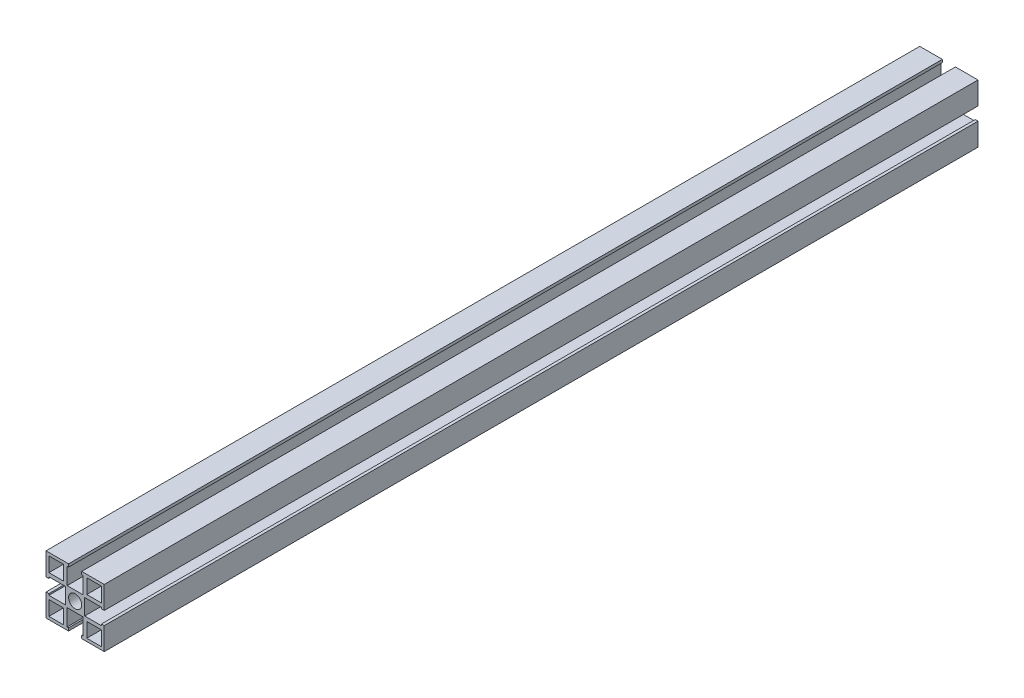
SolidWorks part; units mm, degrees
ref_plane "前视基准面" through (0, 0, 0) normal (0, 0, 1) x (1, 0, 0)
ref_plane "上视基准面" through (0, 0, 0) normal (0, 1, 0) x (1, 0, 0)
ref_plane "右视基准面" through (0, 0, 0) normal (1, 0, 0) x (0, 0, -1)
sketch "草图1" plane through (0, 0, 0) normal (0, 0, 1) x (1, 0, 0)
  line L0 (-2.3693, 20) -> (20, 20) construction
  line L1 (0, 0) -> (15.5, 0)
  line L2 (0, 0) -> (0, 15.5)
  line L3 (0, 40) -> (15.5, 40)
  line L4 (40, 0) -> (40, 15.5)
  line L5 (20, -2.0156) -> (20, 42.823) construction
  line L6 (24.5, 40) -> (40, 40)
  line L7 (14.5, 26.5504) -> (25.5, 26.5504)
  line L8 (14.5, 26.5504) -> (14.5, 38.0504)
  line L9 (2, 38) -> (12, 38)
  line L10 (2, 38) -> (2, 28)
  line L11 (2, 28) -> (12, 28)
  line L12 (12, 38) -> (12, 28)
  line L13 (2, 2) -> (12, 2)
  line L14 (2, 2) -> (2, 12)
  line L15 (2, 12) -> (12, 12)
  line L16 (12, 2) -> (12, 12)
  line L17 (38, 38) -> (28, 38)
  line L18 (38, 38) -> (38, 28)
  line L19 (38, 28) -> (28, 28)
  line L20 (28, 38) -> (28, 28)
  line L21 (38, 2) -> (28, 2)
  line L22 (38, 2) -> (38, 12)
  line L23 (38, 12) -> (28, 12)
  line L24 (28, 2) -> (28, 12)
  line L25 (14.5, 38.0504) -> (15.5, 38.0504)
  line L26 (25.5, 26.5504) -> (25.5, 38.0504)
  line L27 (24.5, 38.0504) -> (25.5, 38.0504)
  line L28 (15.5, 38.0504) -> (15.5, 40)
  line L29 (24.5, 1.9496) -> (24.5, 0)
  line L30 (24.5, 38.0504) -> (24.5, 40)
  line L31 (15.5, 1.9496) -> (15.5, 0)
  line L32 (24.5, 1.9496) -> (25.5, 1.9496)
  line L33 (25.5, 13.4496) -> (25.5, 1.9496)
  line L34 (14.5, 1.9496) -> (15.5, 1.9496)
  line L35 (14.5, 13.4496) -> (14.5, 1.9496)
  line L36 (14.5, 13.4496) -> (25.5, 13.4496)
  line L37 (24.5, 0) -> (40, 0)
  line L38 (1.9496, 15.5) -> (0, 15.5)
  line L39 (1.9496, 24.5) -> (0, 24.5)
  line L40 (1.9496, 15.5) -> (1.9496, 14.5)
  line L41 (13.4496, 14.5) -> (1.9496, 14.5)
  line L42 (1.9496, 25.5) -> (1.9496, 24.5)
  line L43 (13.4496, 25.5) -> (1.9496, 25.5)
  line L44 (13.4496, 25.5) -> (13.4496, 14.5)
  line L45 (26.5504, 25.5) -> (26.5504, 14.5)
  line L46 (26.5504, 25.5) -> (38.0504, 25.5)
  line L47 (38.0504, 25.5) -> (38.0504, 24.5)
  line L48 (26.5504, 14.5) -> (38.0504, 14.5)
  line L49 (38.0504, 15.5) -> (38.0504, 14.5)
  line L50 (38.0504, 24.5) -> (40, 24.5)
  line L51 (38.0504, 15.5) -> (40, 15.5)
  line L52 (0, 24.5) -> (0, 40)
  line L53 (40, 24.5) -> (40, 40)
  circle A0 centre (20, 20) radius 4.5
  point P60 (20, 20)
  dimension "D3" = 9
  dimension "D1" = 40
  dimension "D2" = 40
  dimension "D4" = 10
  dimension "D5" = 10
  dimension "D6" = 10
  dimension "D7" = 10
  dimension "D8" = 10
  dimension "D9" = 10
  dimension "D10" = 10
  dimension "D11" = 10
  dimension "D12" = 11.5
  dimension "D13" = 11
  dimension "D15" = 5.5
  dimension "D16" = 4.5
  dimension "D17" = 4.5
  dimension "D18" = 2
extrude "凸台-拉伸1" add sketch "草图1" along normal blind 600
